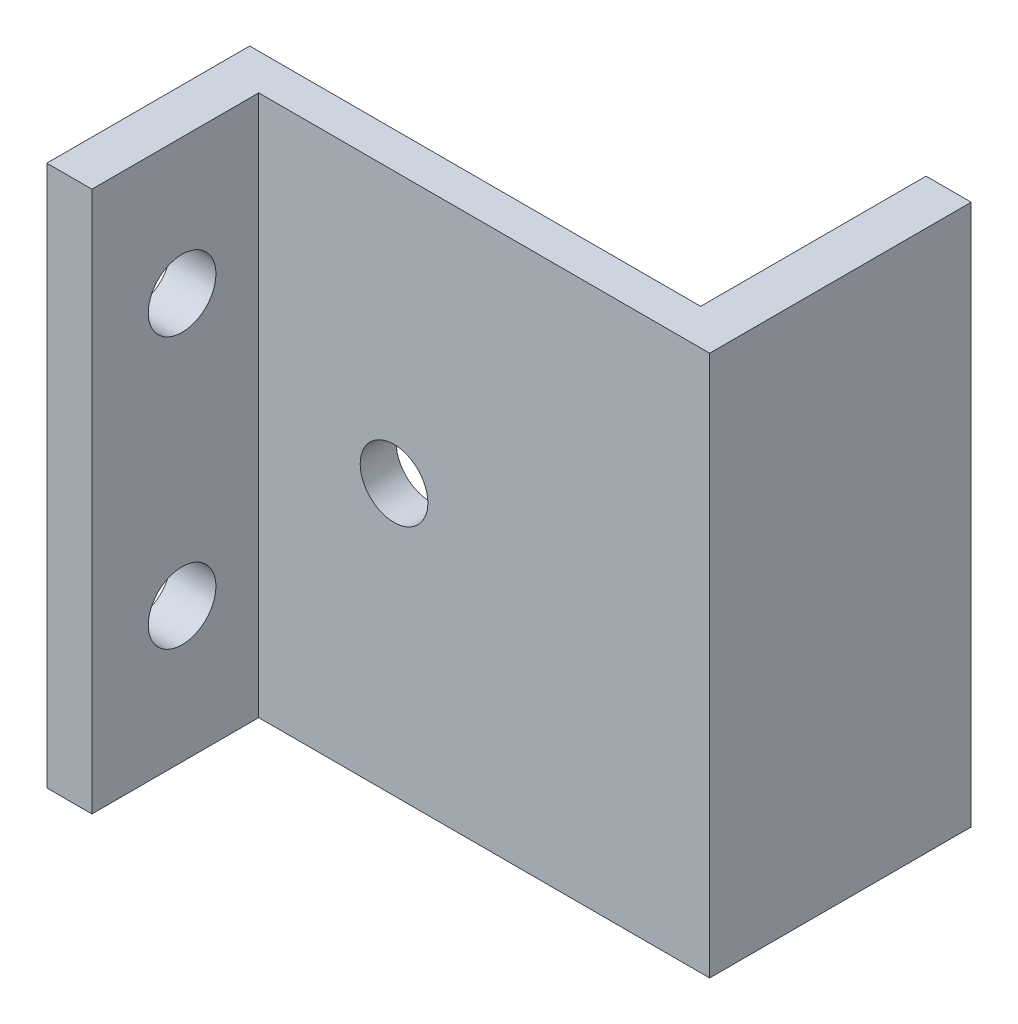
SolidWorks part; units mm, degrees
ref_plane "Plano frontal" through (0, 0, 0) normal (0, 0, 1) x (1, 0, 0)
ref_plane "Plano superior" through (0, 0, 0) normal (0, 1, 0) x (1, 0, 0)
ref_plane "Plano direito" through (0, 0, 0) normal (1, 0, 0) x (0, 0, -1)
sketch "Esboço1" plane through (0, 0, 0) normal (0, 1, 0) x (1, 0, 0)
  line L0 (0, 0) -> (0, -7.4)
  line L1 (0, -7.4) -> (2, -7.4)
  line L2 (2, -7.4) -> (2, 0)
  line L3 (2, 0) -> (22, 0)
  line L4 (22, 0) -> (22, 11.6)
  line L5 (22, 11.6) -> (20, 11.6)
  line L6 (20, 11.6) -> (20, 1.6)
  line L7 (20, 1.6) -> (0, 1.6)
  line L8 (0, 1.6) -> (0, 0)
  dimension "D1" = 2
  dimension "D2" = 20
  dimension "D3" = 20
  dimension "D4" = 10
  dimension "D5" = 9
  dimension "D6" = 1.6
extrude "Ressalto-extrusão2" add sketch "Esboço1" along normal blind 24
sketch "Esboço2" plane through (0, 0, 0) normal (-1, 0, 0) x (0, 0, 1)
  line L0 (7.4, 24) -> (7.4, 0) construction
  line L2 (-1.6, 24) -> (7.4, 24) construction
  circle A0 centre (3.4, 18) radius 1.5
  circle A1 centre (3.4, 6) radius 1.5
  dimension "D3" = 3
  dimension "D4" = 3
  dimension "D1" = 4
  dimension "D2" = 4
  dimension "D5" = 12
  dimension "D6" = 6
extrude "Corte-extrusão1" cut sketch "Esboço2" against normal blind 24
ref_plane "Plano1" through (0, 0, -1.6) normal (-1, 0, 0) x (0, 0, 1)
sketch "Esboço6" plane through (0, 0, -1.6) normal (0, 0, -1) x (-1, 0, 0)
  line L1 (0, 24) -> (0, 0) construction
  circle A1 centre (-8, 12) radius 1.5
  dimension "D3" = 3
  dimension "D1" = 8
extrude "Corte-extrusão2" cut sketch "Esboço6" against normal blind 13
